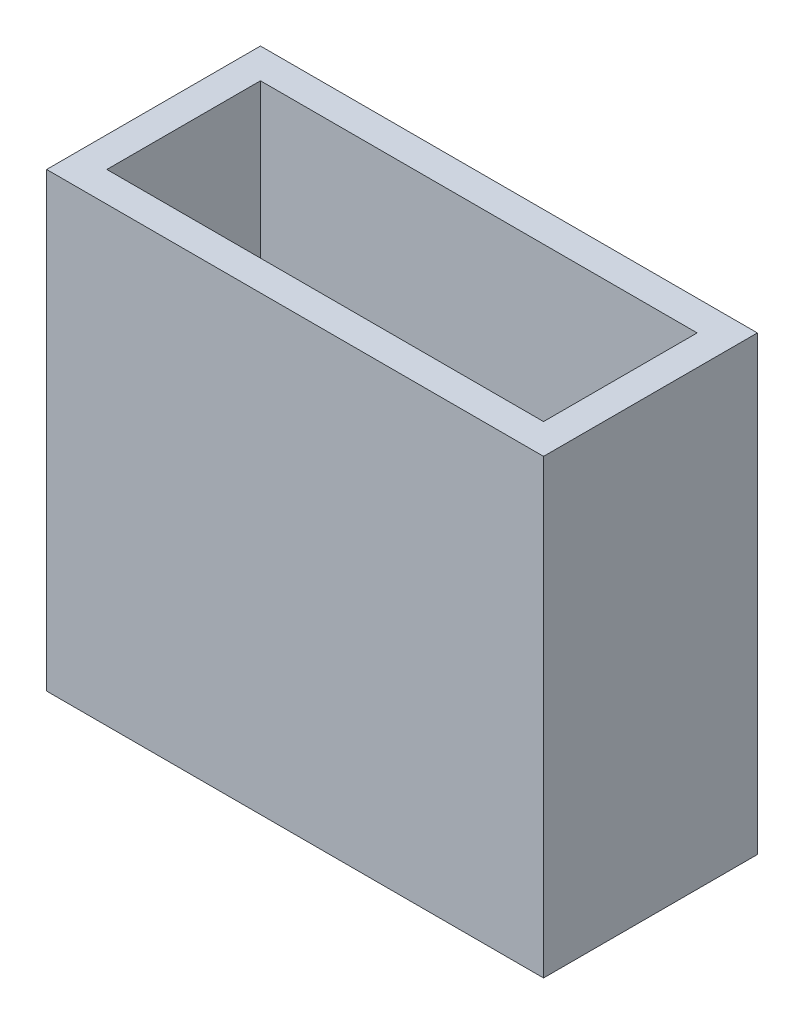
SolidWorks part; units mm, degrees
ref_plane "Front Plane" through (0, 0, 0) normal (0, 0, 1) x (1, 0, 0)
ref_plane "Top Plane" through (0, 0, 0) normal (0, 1, 0) x (1, 0, 0)
ref_plane "Right Plane" through (0, 0, 0) normal (1, 0, 0) x (0, 0, -1)
sketch "Sketch1" plane through (0, 0, 0) normal (0, 1, 0) x (1, 0, 0)
  line L1 (-14.5, -5.1) -> (14.5, -5.1)
  line L2 (-14.5, -5.1) -> (-14.5, 5.1)
  line L3 (-14.5, 5.1) -> (14.5, 5.1)
  line L4 (14.5, -5.1) -> (14.5, 5.1)
  line L5 (-14.5, -5.1) -> (14.5, 5.1) construction
  line L6 (-14.5, 5.1) -> (14.5, -5.1) construction
  line L7 (-16.5, -7.1) -> (16.5, -7.1)
  line L8 (-16.5, -7.1) -> (-16.5, 7.1)
  line L9 (-16.5, 7.1) -> (16.5, 7.1)
  line L10 (16.5, -7.1) -> (16.5, 7.1)
  line L11 (-16.5, -7.1) -> (16.5, 7.1) construction
  line L12 (-16.5, 7.1) -> (16.5, -7.1) construction
  point P0 (0, 0)
  point P6 (0, 0)
  dimension "D1" = 29
  dimension "D2" = 10.2
  dimension "D3" = 2
  dimension "D4" = 2
extrude "Boss-Extrude1" add sketch "Sketch1" along normal blind 30
sketch "Sketch4" plane through (0, 30, 0) normal (0, 1, 0) x (1, 0, 0)
  line L1 (-14.5, 5.1) -> (14.5, 5.1)
  line L2 (-14.5, 5.1) -> (-14.5, -5.1)
  line L3 (-14.5, -5.1) -> (14.5, -5.1)
  line L4 (14.5, 5.1) -> (14.5, -5.1)
extrude "Boss-Extrude2" add sketch "Sketch4" against normal blind 2 from offset 14 offset against normal yes
sketch "Sketch5" plane through (0, 16, 0) normal (0, 1, 0) x (1, 0, 0)
  line L0 (-10.425, -0.55) -> (-10.425, 0.05)
  line L1 (-12.675, -2.7) -> (-12.075, -2.7)
  line L2 (-12.675, -2.7) -> (-12.675, -3.3)
  line L3 (-12.675, -3.3) -> (-12.075, -3.3)
  line L4 (-12.075, -2.7) -> (-12.075, -3.3)
  line L5 (-12.675, -0.55) -> (-12.075, -0.55)
  line L6 (-12.675, -0.55) -> (-12.675, 0.05)
  line L7 (-12.675, 0.05) -> (-12.075, 0.05)
  line L8 (-12.075, -0.55) -> (-12.075, 0.05)
  line L9 (-10.425, -0.55) -> (-9.825, -0.55)
  line L10 (-9.825, -0.55) -> (-9.825, 0.05)
  line L11 (-10.425, 0.05) -> (-9.825, 0.05)
  line L12 (-10.425, -2.7) -> (-10.425, -3.3)
  line L13 (-10.425, -2.7) -> (-9.825, -2.7)
  line L14 (-9.825, -2.7) -> (-9.825, -3.3)
  line L15 (-10.425, -3.3) -> (-9.825, -3.3)
  line L16 (-8.175, -0.55) -> (-8.175, 0.05)
  line L17 (-8.175, -0.55) -> (-7.575, -0.55)
  line L18 (-7.575, -0.55) -> (-7.575, 0.05)
  line L19 (-8.175, 0.05) -> (-7.575, 0.05)
  line L20 (-8.175, -2.7) -> (-8.175, -3.3)
  line L21 (-8.175, -2.7) -> (-7.575, -2.7)
  line L22 (-7.575, -2.7) -> (-7.575, -3.3)
  line L23 (-8.175, -3.3) -> (-7.575, -3.3)
  line L24 (-5.925, -0.55) -> (-5.925, 0.05)
  line L25 (-5.925, -0.55) -> (-5.325, -0.55)
  line L26 (-5.325, -0.55) -> (-5.325, 0.05)
  line L27 (-5.925, 0.05) -> (-5.325, 0.05)
  line L28 (-5.925, -2.7) -> (-5.925, -3.3)
  line L29 (-5.925, -2.7) -> (-5.325, -2.7)
  line L30 (-5.325, -2.7) -> (-5.325, -3.3)
  line L31 (-5.925, -3.3) -> (-5.325, -3.3)
  line L32 (-3.675, -0.55) -> (-3.675, 0.05)
  line L33 (-3.675, -0.55) -> (-3.075, -0.55)
  line L34 (-3.075, -0.55) -> (-3.075, 0.05)
  line L35 (-3.675, 0.05) -> (-3.075, 0.05)
  line L36 (-3.675, -2.7) -> (-3.675, -3.3)
  line L37 (-3.675, -2.7) -> (-3.075, -2.7)
  line L38 (-3.075, -2.7) -> (-3.075, -3.3)
  line L39 (-3.675, -3.3) -> (-3.075, -3.3)
  line L40 (-1.425, -0.55) -> (-1.425, 0.05)
  line L41 (-1.425, -0.55) -> (-0.825, -0.55)
  line L42 (-0.825, -0.55) -> (-0.825, 0.05)
  line L43 (-1.425, 0.05) -> (-0.825, 0.05)
  line L44 (-1.425, -2.7) -> (-1.425, -3.3)
  line L45 (-1.425, -2.7) -> (-0.825, -2.7)
  line L46 (-0.825, -2.7) -> (-0.825, -3.3)
  line L47 (-1.425, -3.3) -> (-0.825, -3.3)
  line L48 (0.825, -0.55) -> (0.825, 0.05)
  line L49 (0.825, -0.55) -> (1.425, -0.55)
  line L50 (1.425, -0.55) -> (1.425, 0.05)
  line L51 (0.825, 0.05) -> (1.425, 0.05)
  line L52 (0.825, -2.7) -> (0.825, -3.3)
  line L53 (0.825, -2.7) -> (1.425, -2.7)
  line L54 (1.425, -2.7) -> (1.425, -3.3)
  line L55 (0.825, -3.3) -> (1.425, -3.3)
  line L56 (3.075, -0.55) -> (3.075, 0.05)
  line L57 (3.075, -0.55) -> (3.675, -0.55)
  line L58 (3.675, -0.55) -> (3.675, 0.05)
  line L59 (3.075, 0.05) -> (3.675, 0.05)
  line L60 (3.075, -2.7) -> (3.075, -3.3)
  line L61 (3.075, -2.7) -> (3.675, -2.7)
  line L62 (3.675, -2.7) -> (3.675, -3.3)
  line L63 (3.075, -3.3) -> (3.675, -3.3)
  line L64 (5.325, -0.55) -> (5.325, 0.05)
  line L65 (5.325, -0.55) -> (5.925, -0.55)
  line L66 (5.925, -0.55) -> (5.925, 0.05)
  line L67 (5.325, 0.05) -> (5.925, 0.05)
  line L68 (5.325, -2.7) -> (5.325, -3.3)
  line L69 (5.325, -2.7) -> (5.925, -2.7)
  line L70 (5.925, -2.7) -> (5.925, -3.3)
  line L71 (5.325, -3.3) -> (5.925, -3.3)
  line L72 (7.575, -0.55) -> (7.575, 0.05)
  line L73 (7.575, -0.55) -> (8.175, -0.55)
  line L74 (8.175, -0.55) -> (8.175, 0.05)
  line L75 (7.575, 0.05) -> (8.175, 0.05)
  line L76 (7.575, -2.7) -> (7.575, -3.3)
  line L77 (7.575, -2.7) -> (8.175, -2.7)
  line L78 (8.175, -2.7) -> (8.175, -3.3)
  line L79 (7.575, -3.3) -> (8.175, -3.3)
  line L80 (9.825, -0.55) -> (9.825, 0.05)
  line L81 (9.825, -0.55) -> (10.425, -0.55)
  line L82 (10.425, -0.55) -> (10.425, 0.05)
  line L83 (9.825, 0.05) -> (10.425, 0.05)
  line L84 (9.825, -2.7) -> (9.825, -3.3)
  line L85 (9.825, -2.7) -> (10.425, -2.7)
  line L86 (10.425, -2.7) -> (10.425, -3.3)
  line L87 (9.825, -3.3) -> (10.425, -3.3)
  line L88 (12.075, -0.55) -> (12.075, 0.05)
  line L89 (12.075, -0.55) -> (12.675, -0.55)
  line L90 (12.675, -0.55) -> (12.675, 0.05)
  line L91 (12.075, 0.05) -> (12.675, 0.05)
  line L92 (12.075, -2.7) -> (12.075, -3.3)
  line L93 (12.075, -2.7) -> (12.675, -2.7)
  line L94 (12.675, -2.7) -> (12.675, -3.3)
  line L95 (12.075, -3.3) -> (12.675, -3.3)
  line L96 (-1.125, 0.05) -> (1.125, 0.05) construction
  line L97 (-14.5, -5.1) -> (14.5, -5.1) construction
  point P4 (-12.675, -3)
  point P9 (-12.675, -0.25)
  point P10 (0, 0.05)
  dimension "D1" = 0.6
  dimension "D2" = 2.75
  dimension "D4" = 2.25
  dimension "D5" = 1.8
  dimension "D3" = 12
extrude "Cut-Extrude1" cut sketch "Sketch5" against normal through all both and the other way through all
